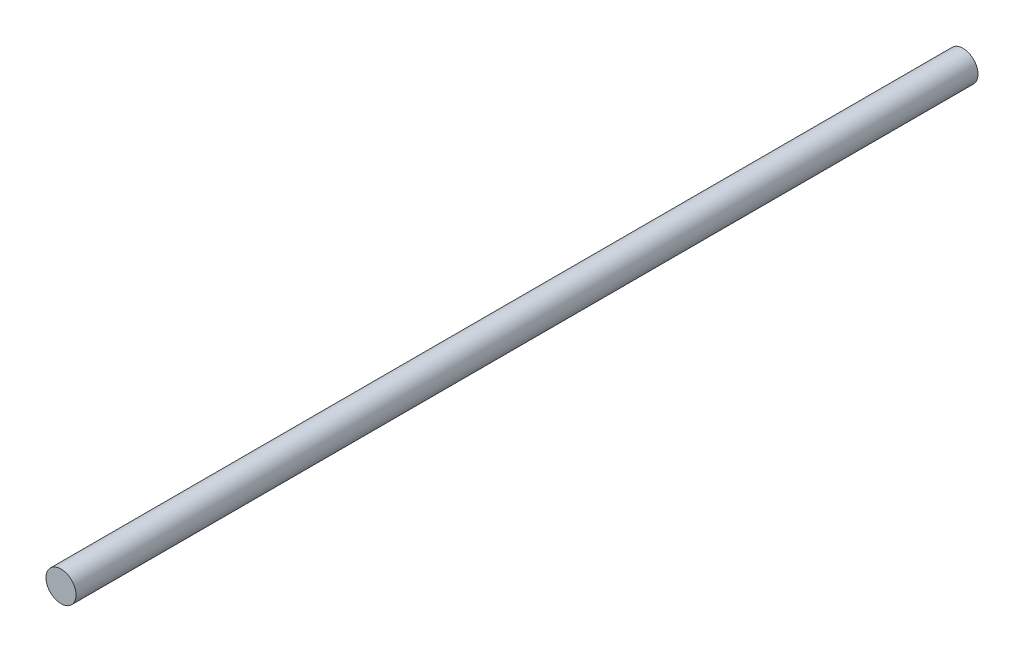
SolidWorks part; units mm, degrees
ref_plane "Front Plane" through (0, 0, 0) normal (0, 0, 1) x (1, 0, 0)
ref_plane "Top Plane" through (0, 0, 0) normal (0, 1, 0) x (1, 0, 0)
ref_plane "Right Plane" through (0, 0, 0) normal (1, 0, 0) x (0, 0, -1)
sketch "Sketch1" plane through (0, 0, 0) normal (0, 0, 1) x (1, 0, 0)
  circle A0 centre (0, 0) radius 2.5
extrude "Boss-Extrude1" add sketch "Sketch1" along normal blind 150
